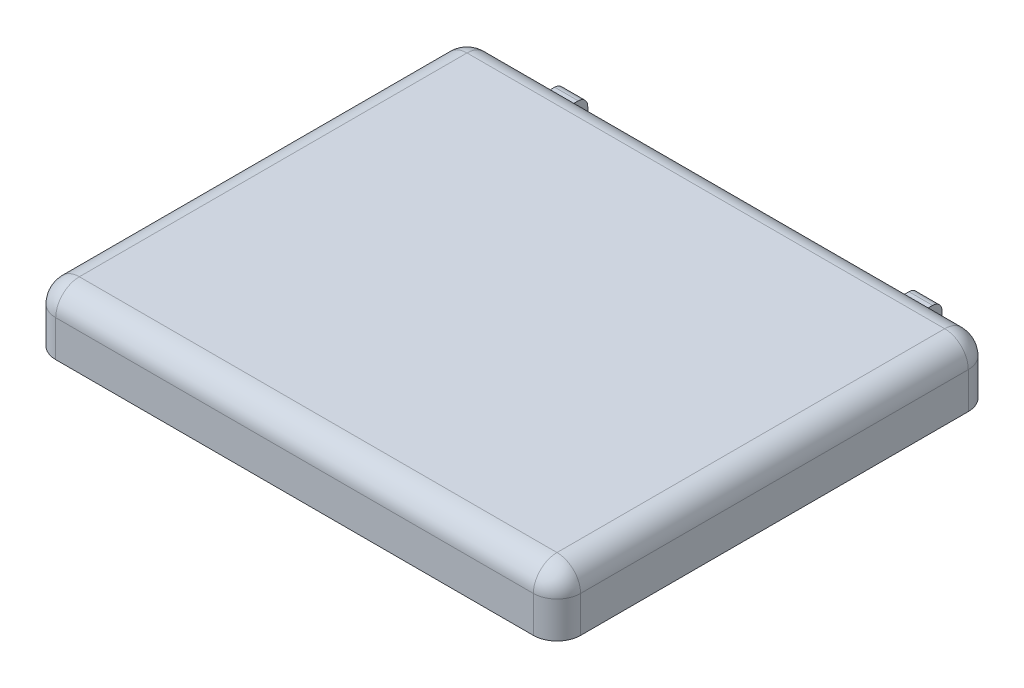
SolidWorks part; units mm, degrees
material "Acrylic (Medium-high impact)"
ref_plane "Front Plane" through (0, 0, 0) normal (0, 0, 1) x (1, 0, 0)
ref_plane "Top Plane" through (0, 0, 0) normal (0, 1, 0) x (1, 0, 0)
ref_plane "Right Plane" through (0, 0, 0) normal (1, 0, 0) x (0, 0, -1)
sketch "Sketch1" plane through (0, 0, 0) normal (0, 1, 0) x (1, 0, 0)
  line L1 (111.125, -92.075) -> (-111.125, -92.075)
  line L2 (111.125, -92.075) -> (111.125, 92.075)
  line L3 (111.125, 92.075) -> (-111.125, 92.075)
  line L4 (-111.125, -92.075) -> (-111.125, 92.075)
  line L5 (111.125, -92.075) -> (-111.125, 92.075) construction
  line L6 (111.125, 92.075) -> (-111.125, -92.075) construction
  point P0 (0, 0)
  dimension "D1" = 222.25
  dimension "D2" = 184.15
ref_plane "Plane1" through (0, 25.4, 0) normal (0, 1, 0) x (1, 0, 0)
sketch "Sketch2" plane through (0, 25.4, 0) normal (0, 1, 0) x (1, 0, 0)
  line L1 (111.125, 92.075) -> (-111.125, 92.075)
  line L2 (111.125, 92.075) -> (111.125, -92.075)
  line L3 (111.125, -92.075) -> (-111.125, -92.075)
  line L4 (-111.125, 92.075) -> (-111.125, -92.075)
  line L5 (111.125, 92.075) -> (-111.125, -92.075) construction
  line L6 (111.125, -92.075) -> (-111.125, 92.075) construction
  point P0 (0, 0)
  dimension "D1" = 184.15
  dimension "D2" = 222.25
loft "Loft3" add profiles "Sketch1", "Sketch2"
fillet "Fillet1" radius 10 8 edges
shell "Shell1" thickness 3.175
ref_plane "Plane6" through (70, 0, 0) normal (1, 0, 0) x (0, 0, -1)
sketch "Sketch7" plane through (70, 0, 0) normal (1, 0, 0) x (0, 0, -1)
  line L1 (92.075, 15.4) -> (102.075, 15.4)
  line L2 (92.075, 15.4) -> (92.075, -23.6)
  line L3 (92.075, -23.6) -> (102.075, -23.6)
  line L4 (82.075, 0) -> (92.075, 0)
  line L5 (92.075, 0) -> (92.075, 15.4)
  line L6 (92.075, 15.4) -> (82.075, 15.4)
  line L7 (82.075, 15.4) -> (82.075, 0)
  line L8 (82.075, 0) -> (92.075, 0)
  line L9 (92.075, 0) -> (92.075, 15.4)
  line L10 (92.075, 15.4) -> (82.075, 15.4)
  line L11 (82.075, 15.4) -> (82.075, 0)
  line L12 (102.075, 15.4) -> (102.075, -23.6)
  circle A0 centre (95.075, -18.2245) radius 1
  dimension "D4" = 2
  dimension "D2" = 39
  dimension "D3" = 10
  dimension "D5" = 7
  dimension "D6" = 5.3755
  dimension "D1" = 0
extrude "Boss-Extrude1" add sketch "Sketch7" along normal blind 10 contours L12 L1 L2 L3 A0
fillet "Fillet2" radius 4 5 edges at (75, -23.6, -92.075) (80, -23.6, -97.075) (70, -23.6, -97.075) (75, -23.6, -102.075) (75, 15.4, -102.075)
mirror "Mirror1" about plane through (0, 0, 0) normal (1, 0, 0) of "Boss-Extrude1", "Fillet2"
